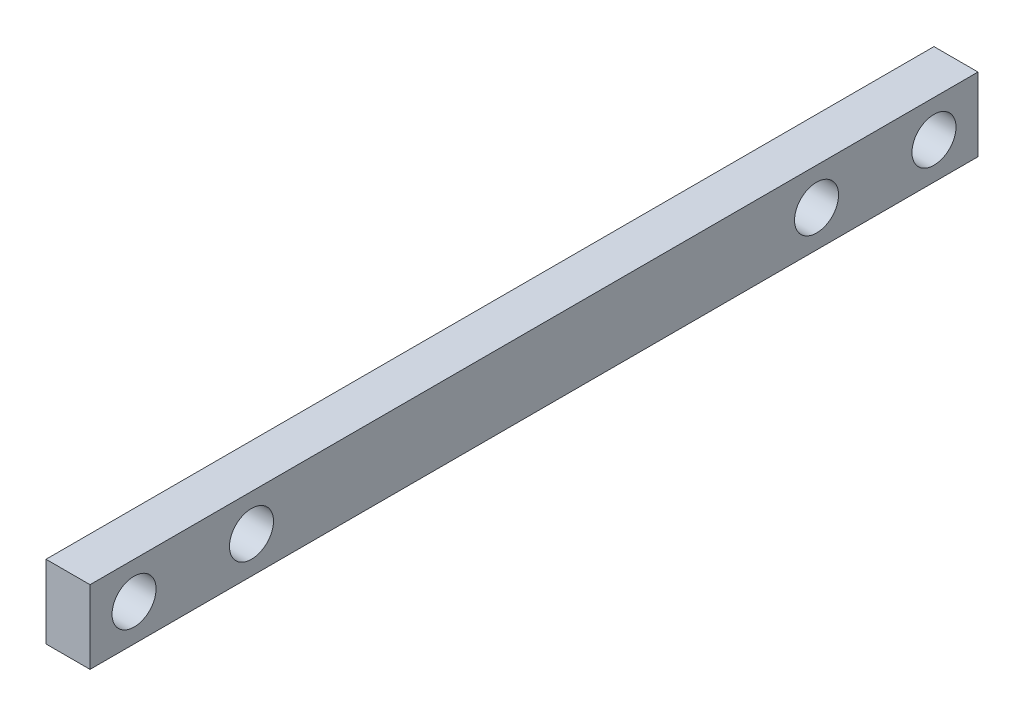
SolidWorks part; units mm, degrees
ref_plane "Front Plane" through (0, 0, 0) normal (0, 0, 1) x (1, 0, 0)
ref_plane "Top Plane" through (0, 0, 0) normal (0, 1, 0) x (1, 0, 0)
ref_plane "Right Plane" through (0, 0, 0) normal (1, 0, 0) x (0, 0, -1)
sketch "Sketch1" plane through (0, 0, 0) normal (1, 0, 0) x (0, 0, -1)
  line L1 (-30.25, -2.5) -> (30.25, -2.5)
  line L2 (-30.25, -2.5) -> (-30.25, 2.5)
  line L3 (-30.25, 2.5) -> (30.25, 2.5)
  line L4 (30.25, -2.5) -> (30.25, 2.5)
  line L5 (0, 2.5) -> (0, -2.5) construction
  line L6 (-30.25, 0) -> (30.25, 0) construction
  circle A0 centre (-27.25, 0) radius 1.5
  circle A1 centre (-19.25, 0) radius 1.5
  circle A2 centre (27.25, 0) radius 1.5
  circle A3 centre (19.25, 0) radius 1.5
  point P0 (0, 0)
  point P18 (0, 0)
  dimension "D5" = 3
  dimension "D6" = 3
  dimension "D9" = 3
  dimension "D10" = 3
  dimension "D2" = 5
  dimension "D3" = 3
  dimension "D4" = 8
  dimension "D7" = 54.5
  dimension "D8" = 8
  dimension "D11" = 3
extrude "Boss-Extrude1" add sketch "Sketch1" along normal blind 3
